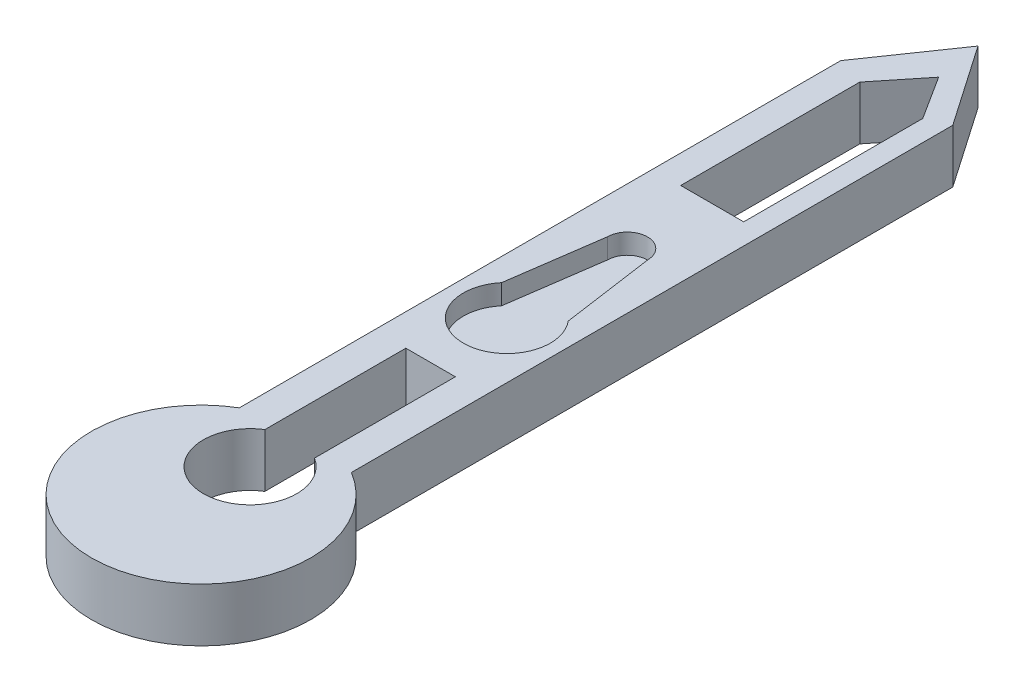
SolidWorks part; units mm, degrees
ref_plane "Front Plane" through (0, 0, 0) normal (0, 0, 1) x (1, 0, 0)
ref_plane "Top Plane" through (0, 0, 0) normal (0, 1, 0) x (1, 0, 0)
ref_plane "Right Plane" through (0, 0, 0) normal (1, 0, 0) x (0, 0, -1)
sketch "Sketch1" plane through (0, 0, 0) normal (0, 1, 0) x (1, 0, 0)
  line L0 (0, 0) -> (0, 18) construction
  circle A0 centre (0, 0) radius 6 construction
  dimension "D1" = 12
  dimension "D2" = 18
sketch "Sketch2" plane through (0, 0, 0) normal (0, 1, 0) x (1, 0, 0)
  line L0 (0, 0) -> (0, 70) construction
  line L2 (-15, 95) -> (15, 95)
  line L3 (-15, 95) -> (-15, 45)
  line L4 (-15, 45) -> (15, 45)
  line L5 (15, 95) -> (15, 45)
  line L6 (-15, 95) -> (15, 45) construction
  line L7 (-15, 45) -> (15, 95) construction
  line L8 (-8.3638, 45.669) -> (8.3638, 45.669)
  line L9 (-8.3638, 45.669) -> (-8.3638, -45.669)
  line L10 (-8.3638, -45.669) -> (8.3638, -45.669)
  line L11 (8.3638, 45.669) -> (8.3638, -45.669)
  line L12 (-8.3638, 45.669) -> (8.3638, -45.669) construction
  line L13 (-8.3638, -45.669) -> (8.3638, 45.669) construction
  circle A1 centre (0, -45.669) radius 16.3754
  dimension "D1" = 70
  dimension "D2" = 50
  dimension "D3" = 30
extrude "Boss-Extrude1" add sketch "Sketch2" along normal blind 8 contours A1 L11 L4 L9
sketch "Sketch4" plane through (0, 8, 0) normal (0, 1, 0) x (1, 0, 0)
  line L0 (0, 0) -> (0, 18) construction
  line L1 (0, 0) -> (0, 18) construction
  line L2 (4.5, 3.9686) -> (-4.5, 3.9686) construction
  line L3 (4.5, 3.9686) -> (2.5, 18)
  line L4 (-2.5, 18) -> (-4.5, 3.9686)
  circle A0 centre (0, 0) radius 6 construction
  circle A1 centre (0, 0) radius 6 construction
  circle A2 centre (0, 18) radius 2.5 construction
  arc A3 (2.5, 18) -> (-2.5, 18) centre (0, 18) ccw
  arc A4 (4.5, 3.9686) -> (-4.5, 3.9686) centre (0, 0) cw
  dimension "D1" = 5
  dimension "D2" = 9
sketch "Sketch6" plane through (0, 8, 0) normal (0, 1, 0) x (1, 0, 0)
  line L4 (-2.9998, 18.0371) -> (-4.9744, 4.184)
  line L5 (4.9744, 4.184) -> (2.9998, 18.0371)
  line L6 (-2.9998, 18.0371) -> (-4.9744, 4.184)
  line L7 (4.9744, 4.184) -> (2.9998, 18.0371)
  arc A4 (-4.9744, 4.184) -> (4.9744, 4.184) centre (0, 0) ccw
  arc A5 (2.9998, 18.0371) -> (-2.9998, 18.0371) centre (0, 18) ccw
  arc A6 (-4.9744, 4.184) -> (4.9744, 4.184) centre (0, 0) ccw
  arc A7 (2.9998, 18.0371) -> (-2.9998, 18.0371) centre (0, 18) ccw
  dimension "D1" = 0.5
extrude "Cut-Extrude1" cut sketch "Sketch6" against normal blind 3
sketch "Sketch7" plane through (0, 0, 0) normal (0, -1, 0) x (1, 0, 0)
  line L0 (-15, -70) -> (15, -70) construction
  line L1 (-15, -95) -> (-15, -45) construction
  line L2 (15, -95) -> (15, -45) construction
  line L3 (0, -95) -> (0, -44.3904) construction
  line L4 (-15, -95) -> (15, -95) construction
  line L6 (10.5, -90.5) -> (-10.5, -90.5)
  line L7 (10.5, -90.5) -> (10.5, -49.5)
  line L8 (10.5, -49.5) -> (-10.5, -49.5)
  line L9 (-10.5, -90.5) -> (-10.5, -49.5)
  line L10 (10.5, -90.5) -> (-10.5, -49.5) construction
  line L11 (10.5, -49.5) -> (-10.5, -90.5) construction
  line L12 (-3.5, -58.5) -> (3.5, -58.5)
  line L13 (-3.5, -58.5) -> (-3.5, -40.5)
  line L14 (-3.5, -40.5) -> (3.5, -40.5)
  line L15 (3.5, -58.5) -> (3.5, -40.5)
  line L16 (-3.5, -58.5) -> (3.5, -40.5) construction
  line L17 (-3.5, -40.5) -> (3.5, -58.5) construction
  point P11 (0, -70)
  point P16 (0, -49.5)
  dimension "D1" = 41
  dimension "D2" = 21
  dimension "D3" = 7
  dimension "D4" = 18
extrude "Cut-Extrude2" cut sketch "Sketch7" against normal through all contours L8 L15 L14 L13
sketch "Sketch8" plane through (0, 0, 0) normal (0, -1, 0) x (1, 0, 0)
  line L1 (-23.3316, -27.3586) -> (19.3822, -27.3586)
  line L2 (-23.3316, -27.3586) -> (-23.3316, -99.603)
  line L3 (-23.3316, -99.603) -> (19.3822, -99.603)
  line L4 (19.3822, -27.3586) -> (19.3822, -99.603)
extrude "Cut-Extrude3" cut sketch "Sketch8" against normal through all
sketch "Sketch10" plane through (0, 0, -27.3586) normal (0, 0, -1) x (-1, 0, 0)
  line L4 (-8.3638, 8) -> (-8.3638, 0)
  line L5 (-8.3638, 0) -> (8.3638, 0)
  line L6 (8.3638, 0) -> (8.3638, 8)
  line L7 (8.3638, 8) -> (-8.3638, 8)
  line L8 (-8.3638, 8) -> (-8.3638, 0)
  line L9 (-8.3638, 0) -> (8.3638, 0)
  line L10 (8.3638, 0) -> (8.3638, 8)
  line L11 (8.3638, 8) -> (-8.3638, 8)
  dimension "D1" = 0
extrude "Boss-Extrude3" add sketch "Sketch10" along normal blind 43
sketch "Sketch11" plane through (0, 0, 0) normal (0, -1, 0) x (1, 0, 0)
  line L0 (-8.3638, -58.229) -> (8.3638, -58.229) construction
  line L1 (-8.3638, -70.3586) -> (-8.3638, 31.5906) construction
  line L2 (8.3638, -70.3586) -> (8.3638, 31.5906) construction
  line L3 (-8.3638, -58.229) -> (0, -70.3586)
  line L4 (8.3638, -70.3586) -> (-8.3638, -70.3586) construction
  line L5 (0, -70.3586) -> (8.3638, -58.229)
  line L6 (8.3638, -58.229) -> (14.6348, -58.229)
  line L7 (14.6348, -58.229) -> (14.6348, -78.1243)
  line L8 (14.6348, -78.1243) -> (-16.4865, -78.1243)
  line L9 (-16.4865, -78.1243) -> (-15.8196, -58.229)
  line L10 (-15.8196, -58.229) -> (-8.3638, -58.229)
extrude "Cut-Extrude4" cut sketch "Sketch11" against normal blind 23
sketch "Sketch12" plane through (0, 8, 0) normal (0, 1, 0) x (1, 0, 0)
  line L0 (5.2436, 56.8679) -> (1.0879, 63.3957)
  line L1 (5.2436, 30.1244) -> (-4.1661, 30.1244)
  line L2 (5.2436, 30.1244) -> (5.2436, 56.8679)
  line L3 (5.2436, 56.8679) -> (-4.1661, 56.8679)
  line L4 (-4.1661, 30.1244) -> (-4.1661, 56.8679)
  line L5 (3.7529, -11.4424) -> (-3.6446, -11.4424)
  line L6 (3.7529, -11.4424) -> (3.7529, -32.491)
  line L7 (3.7529, -32.491) -> (-3.6446, -32.491)
  line L8 (-3.6446, -11.4424) -> (-3.6446, -32.491)
  line L9 (1.0879, 63.3957) -> (-4.1661, 56.8679)
  arc A0 (3.7529, -32.491) -> (-3.6446, -32.491) centre (0.0541, -38.4063) cw
extrude "Cut-Extrude5" cut sketch "Sketch12" against normal blind 10 contours L4 L1 L2 L3 | L5 L8 L7 L6 | A0 L7 | L0 L9 L3
